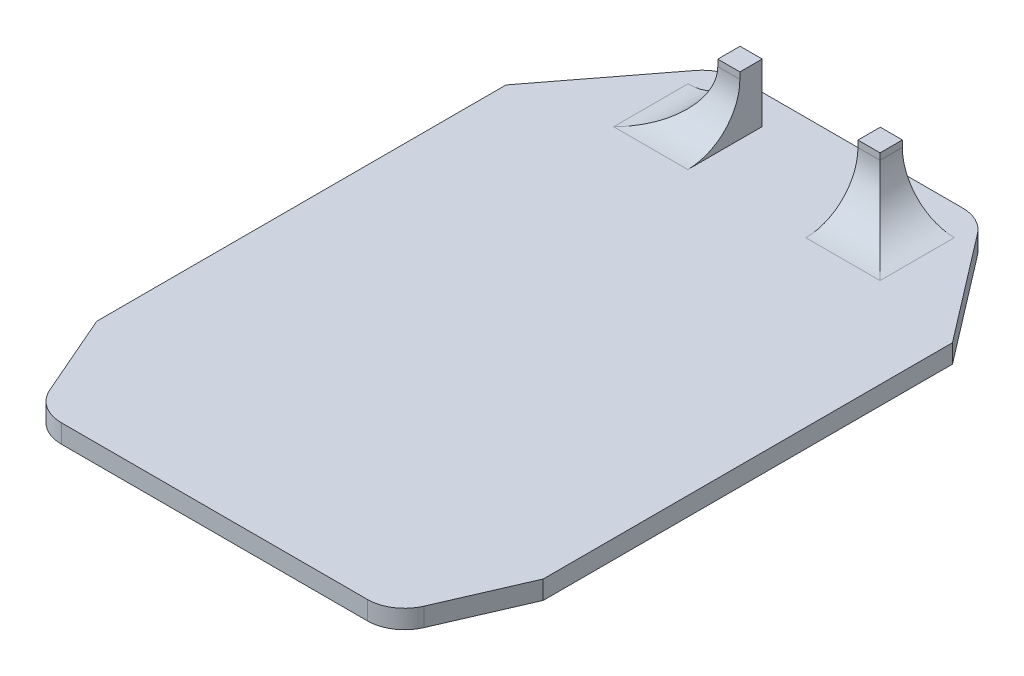
SolidWorks part; units mm, degrees
ref_plane "Front Plane" through (0, 0, 0) normal (0, 0, 1) x (1, 0, 0)
ref_plane "Top Plane" through (0, 0, 0) normal (0, 1, 0) x (1, 0, 0)
ref_plane "Right Plane" through (0, 0, 0) normal (1, 0, 0) x (0, 0, -1)
sketch "Sketch1" plane through (0, 0, 0) normal (0, 1, 0) x (1, 0, 0)
  line L5 (12.7, 141.121) -> (88.9, 141.121)
  line L7 (-25.4, -40.132) -> (-25.4, 99.568)
  line L8 (12.7, 141.121) -> (50.8, 141.121)
  line L9 (50.8, -76.2) -> (50.8, 141.121) construction
  line L10 (114.6748, -68.5529) -> (127, -40.132)
  line L11 (127, -40.132) -> (127, 99.568)
  line L12 (2.6181, 136.144) -> (-25.4, 99.568)
  line L13 (-25.4, 99.568) -> (-25.4, -40.132)
  line L14 (103.0233, -76.2) -> (-1.4233, -76.2)
  line L15 (-13.0748, -68.5529) -> (-25.4, -40.132)
  line L16 (98.9819, 136.144) -> (127, 99.568)
  line L17 (-25.4, 99.568) -> (-25.4, -40.132)
  arc A0 (-1.4233, -76.2) -> (-13.0748, -68.5529) centre (-1.4233, -63.5) cw
  arc A1 (12.7, 141.121) -> (2.6181, 136.144) centre (12.7, 128.421) ccw
  arc A2 (103.0233, -76.2) -> (114.6748, -68.5529) centre (103.0233, -63.5) ccw
  arc A3 (88.9, 141.121) -> (98.9819, 136.144) centre (88.9, 128.421) cw
  point P0 (0, 0)
  point P1 (0, 0)
  dimension "D7" = 12.7
  dimension "D3" = 12.7
  dimension "D1" = 38.1
  dimension "D2" = 76.2
  dimension "D4" = 139.7
  dimension "D5" = 36.068
  dimension "D6" = 41.553
  dimension "D8" = 36.576
  dimension "D9" = 28.4209
extrude "Boss-Extrude1" add sketch "Sketch1" along normal blind 6.35 contours L9 L14 A2 L10 L11 L16 A3 L5 | L14 L9 L5 A1 L12 L7 L15 A0
sketch "Sketch2" plane through (0, 6.35, 0) normal (0, 1, 0) x (1, 0, 0)
  line L0 (50.8, 141.121) -> (50.8, 75.417) construction
  line L1 (12.7, 141.121) -> (88.9, 141.121) construction
  line L2 (23.1013, 141.121) -> (78.4987, 141.121) construction
  line L3 (78.4987, 141.121) -> (78.4987, 130.961) construction
  line L4 (78.4987, 130.961) -> (70.9549, 130.961)
  line L5 (78.4987, 130.961) -> (78.4987, 123.341)
  line L6 (78.4987, 123.341) -> (70.9549, 123.341)
  line L7 (70.9549, 130.961) -> (70.9549, 123.341)
  line L8 (23.1013, 123.341) -> (30.6451, 123.341)
  line L9 (23.1013, 130.961) -> (23.1013, 123.341)
  line L10 (23.1013, 130.961) -> (30.6451, 130.961)
  line L11 (30.6451, 130.961) -> (30.6451, 123.341)
  point P7 (50.8, 141.121)
  dimension "D1" = 55.3974
  dimension "D2" = 10.16
  dimension "D3" = 7.62
  dimension "D4" = 7.5438
  dimension "D5" = 7.5438
extrude "Boss-Extrude2" add sketch "Sketch2" along normal blind 19.9898
fillet "Fillet1" radius 17.78 4 edges at (26.8732, 6.35, -123.341) (74.7268, 6.35, -123.341) (23.1013, 6.35, -127.151) (78.4987, 6.35, -127.151)
sketch "Sketch3" plane through (0, 0, -130.961) normal (0, 0, -1) x (-1, 0, 0)
  line L0 (-75.2983, 6.35) -> (-75.2983, 11.3538) construction
  line L1 (-96.2787, 6.35) -> (-70.9549, 6.35) construction
  line L2 (-70.9549, 26.3398) -> (-70.9549, 6.35) construction
  line L3 (-50.8, 6.35) -> (-50.8, 0) construction
  line L4 (-12.7, 6.35) -> (-88.9, 6.35) construction
  line L5 (-12.7, 0) -> (-88.9, 0) construction
  circle A0 centre (-75.2983, 11.3538) radius 1.3462
  circle A1 centre (-75.2983, 21.3614) radius 1.3462
  circle A2 centre (-26.3017, 11.3538) radius 1.3462
  circle A3 centre (-26.3017, 21.3614) radius 1.3462
  dimension "D3" = 2.6924
  dimension "D5" = 2.6924
  dimension "D1" = 5.0038
  dimension "D2" = 4.3434
  dimension "D4" = 15.0114
  dimension "D6" = 4.3434
extrude "Cut-Extrude1" cut sketch "Sketch3" against normal blind 5.4102
